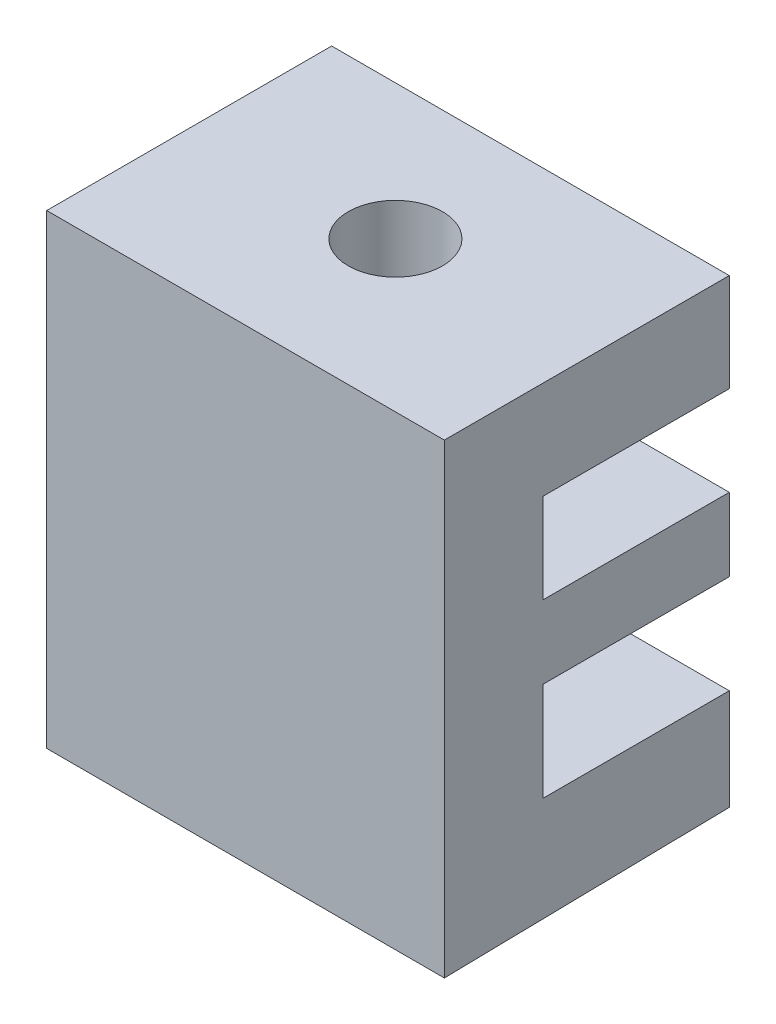
SolidWorks part; units mm, degrees
ref_plane "Front Plane" through (0, 0, 0) normal (0, 0, 1) x (1, 0, 0)
ref_plane "Top Plane" through (0, 0, 0) normal (0, 1, 0) x (1, 0, 0)
ref_plane "Right Plane" through (0, 0, 0) normal (1, 0, 0) x (0, 0, -1)
sketch "Sketch1" plane through (0, 0, 0) normal (1, 0, 0) x (0, 0, -1)
  line L0 (0, 53.7467) -> (0, -49.3863)
  line L1 (0, -49.3863) -> (71.6623, -48.0592)
  line L2 (71.6623, -48.0592) -> (71.6623, -22.6551)
  line L3 (71.6623, -22.6551) -> (24.8353, -22.6551)
  line L4 (24.8353, -22.6551) -> (24.8353, 2.1802)
  line L5 (24.8353, 2.1802) -> (71.6623, 2.1802)
  line L6 (71.6623, 2.1802) -> (71.6623, 20.5697)
  line L7 (71.6623, 20.5697) -> (24.8353, 20.5697)
  line L8 (24.8353, 20.5697) -> (24.8353, 43.1301)
  line L9 (24.8353, 43.1301) -> (71.6623, 43.1301)
  line L10 (71.6623, 43.1301) -> (71.6623, 67.7758)
  line L11 (71.6623, 67.7758) -> (0, 67.7758)
  line L12 (0, 67.7758) -> (0, 53.7467)
extrude "Boss-Extrude1" add sketch "Sketch1" along normal mid plane 100
sketch "Sketch2" plane through (0, 67.7758, 0) normal (0, 1, 0) x (1, 0, 0)
  circle A0 centre (0, 37.6952) radius 11.8385
extrude "Cut-Extrude1" cut sketch "Sketch2" along direction (0, -1, 0) on the side against the normal offset from surface (100.431 mm away) 10
